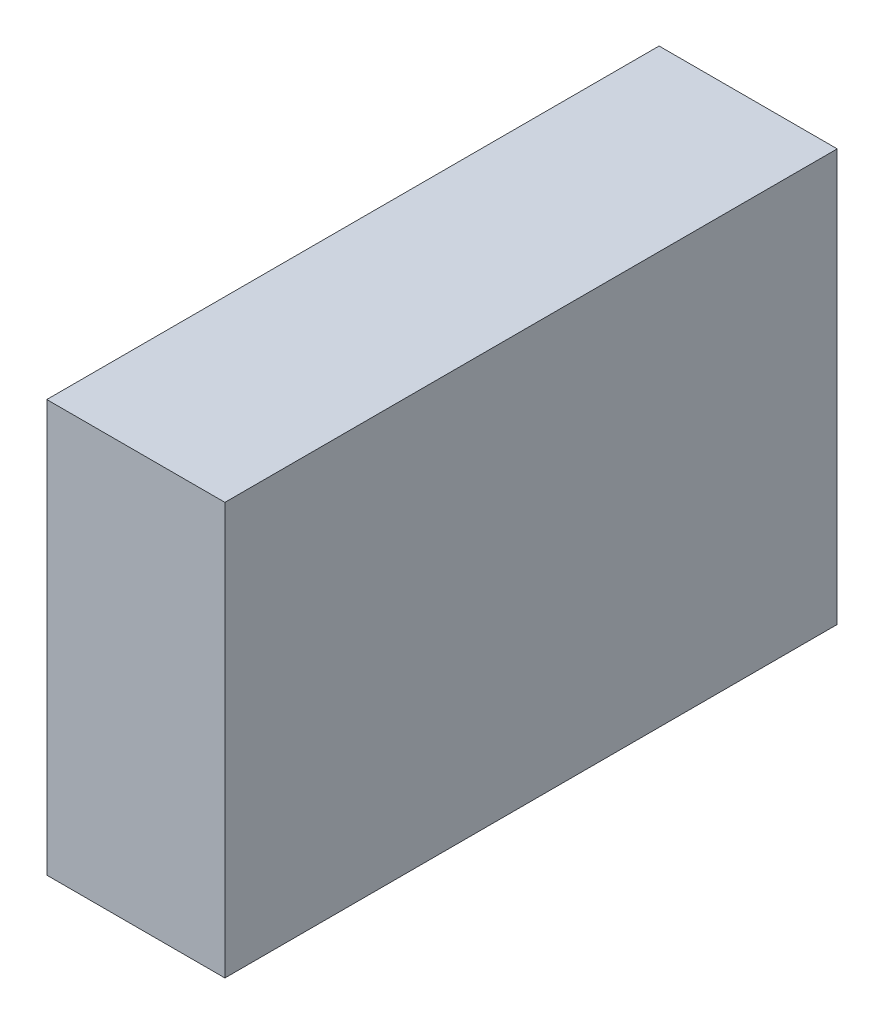
SolidWorks part; units mm, degrees
ref_plane "Front Plane" through (0, 0, 0) normal (0, 0, 1) x (1, 0, 0)
ref_plane "Top Plane" through (0, 0, 0) normal (0, 1, 0) x (1, 0, 0)
ref_plane "Right Plane" through (0, 0, 0) normal (1, 0, 0) x (0, 0, -1)
sketch "Sketch1" plane through (0, 0, 0) normal (1, 0, 0) x (0, 0, -1)
  line L1 (-27.5, 18.5) -> (27.5, 18.5)
  line L2 (-27.5, 18.5) -> (-27.5, -18.5)
  line L3 (-27.5, -18.5) -> (27.5, -18.5)
  line L4 (27.5, 18.5) -> (27.5, -18.5)
  line L5 (-27.5, 18.5) -> (27.5, -18.5) construction
  line L6 (-27.5, -18.5) -> (27.5, 18.5) construction
  point P0 (0, 0)
  dimension "D1" = 55
  dimension "D2" = 37
extrude "Boss-Extrude1" add sketch "Sketch1" along normal blind 16
